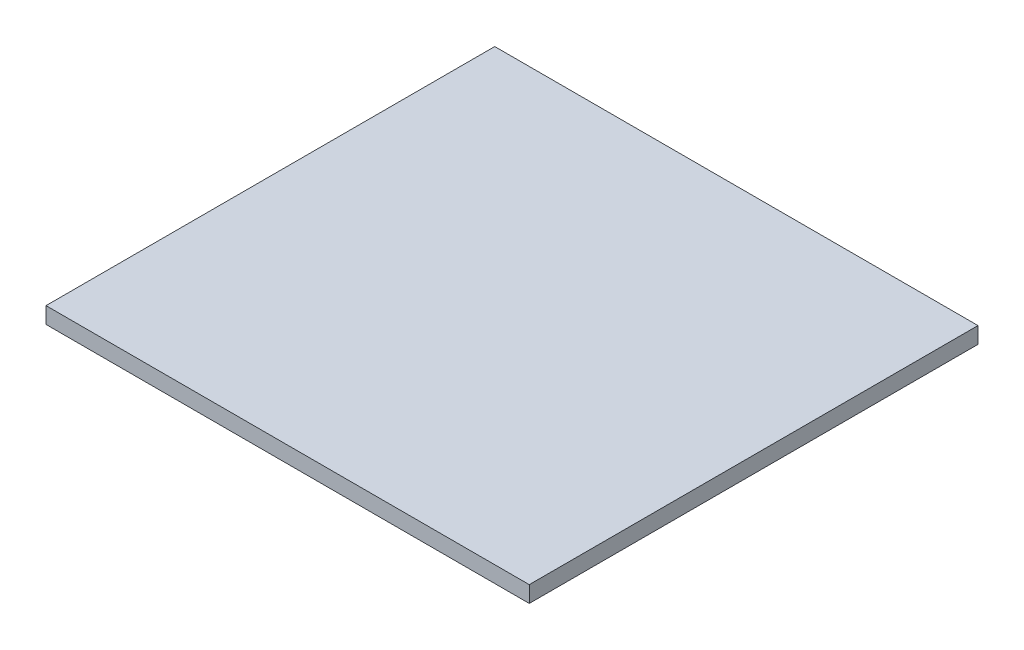
SolidWorks part; units mm, degrees
ref_plane "Front Plane" through (0, 0, 0) normal (0, 0, 1) x (1, 0, 0)
ref_plane "Top Plane" through (0, 0, 0) normal (0, 1, 0) x (1, 0, 0)
ref_plane "Right Plane" through (0, 0, 0) normal (1, 0, 0) x (0, 0, -1)
sketch "Sketch1" plane through (0, 0, 0) normal (0, 1, 0) x (1, 0, 0)
  line L1 (88.9, -82.55) -> (-88.9, -82.55)
  line L2 (88.9, -82.55) -> (88.9, 82.55)
  line L3 (88.9, 82.55) -> (-88.9, 82.55)
  line L4 (-88.9, -82.55) -> (-88.9, 82.55)
  line L5 (88.9, -82.55) -> (-88.9, 82.55) construction
  line L6 (88.9, 82.55) -> (-88.9, -82.55) construction
  point P0 (0, 0)
  dimension "D1" = 177.8
  dimension "D2" = 165.1
extrude "Boss-Extrude1" add sketch "Sketch1" along normal blind 6
